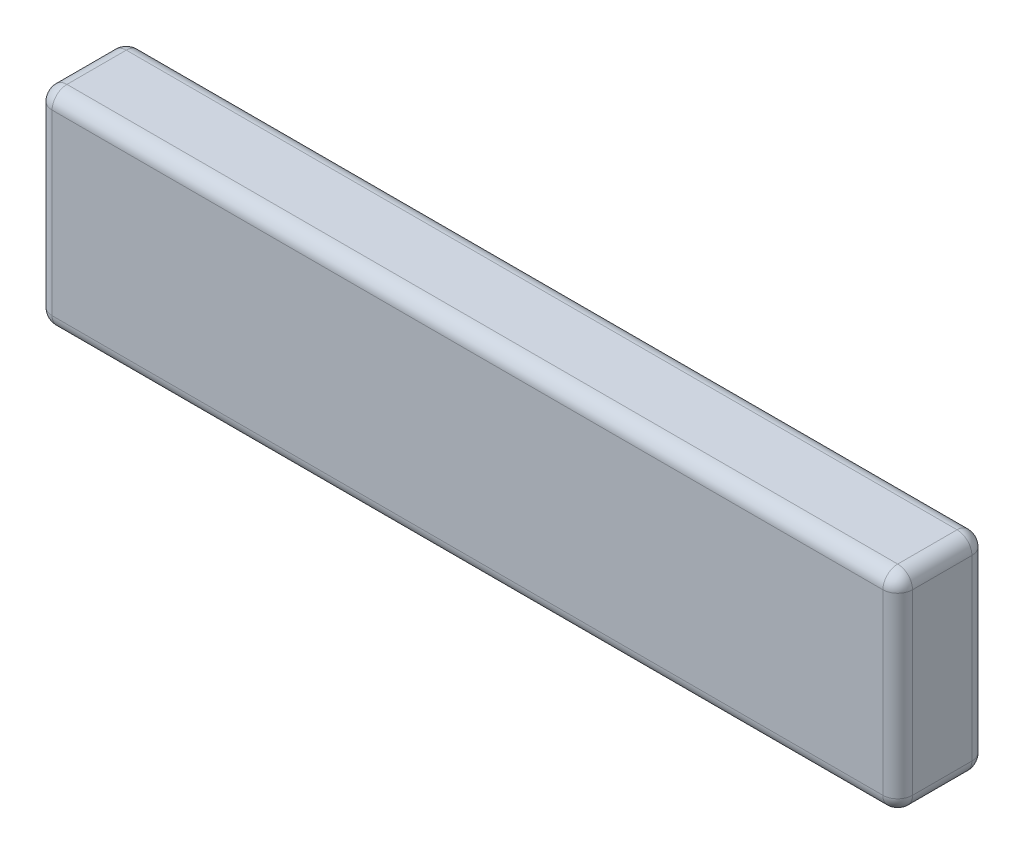
SolidWorks part; units mm, degrees
ref_plane "Front Plane" through (0, 0, 0) normal (0, 0, 1) x (1, 0, 0)
ref_plane "Top Plane" through (0, 0, 0) normal (0, 1, 0) x (1, 0, 0)
ref_plane "Right Plane" through (0, 0, 0) normal (1, 0, 0) x (0, 0, -1)
sketch "Sketch2" plane through (0, 0, 0) normal (1, 0, 0) x (0, 0, -1)
  line L0 (-37.1936, 154.674) -> (-40.3936, 154.674) construction
  line L5 (-40.2936, 147.574) -> (-37.2936, 147.574)
  line L6 (-40.2936, 147.574) -> (-40.2936, 154.574)
  line L7 (-40.2936, 154.574) -> (-37.2936, 154.574)
  line L8 (-37.2936, 147.574) -> (-37.2936, 154.574)
  line L9 (-37.1936, 147.474) -> (-40.3936, 147.474) construction
  line L10 (-37.1936, 154.674) -> (-37.1936, 147.474) construction
  line L11 (-40.3936, 154.674) -> (-40.3936, 147.474) construction
  dimension "D1" = 0.1
  dimension "D2" = 0.1
  dimension "D3" = 0.1
  dimension "D4" = 0.1
extrude "Boss-Extrude1" add sketch "Sketch2" along normal up to surface (29 mm away) from surface at 11.4401
fillet "Fillet1" radius 0.5 4 edges at (25.9401, 154.574, 37.2936) (25.9401, 154.574, 40.2936) (25.9401, 147.574, 37.2936) (25.9401, 147.574, 40.2936)
fillet "Fillet3" radius 0.5 16 edges at (40.4401, 147.7205, 37.44) (40.4401, 147.574, 38.7936) (40.4401, 147.7205, 40.1471) (40.4401, 151.074, 40.2936) (40.4401, 154.4276, 40.1471) (40.4401, 154.574, 38.7936) (40.4401, 154.4276, 37.44) (40.4401, 151.074, 37.2936) (11.4401, 154.4276, 40.1471) (11.4401, 151.074, 40.2936) (11.4401, 147.7205, 40.1471) (11.4401, 147.574, 38.7936) (11.4401, 147.7205, 37.44) (11.4401, 151.074, 37.2936) (11.4401, 154.4276, 37.44) (11.4401, 154.574, 38.7936)
